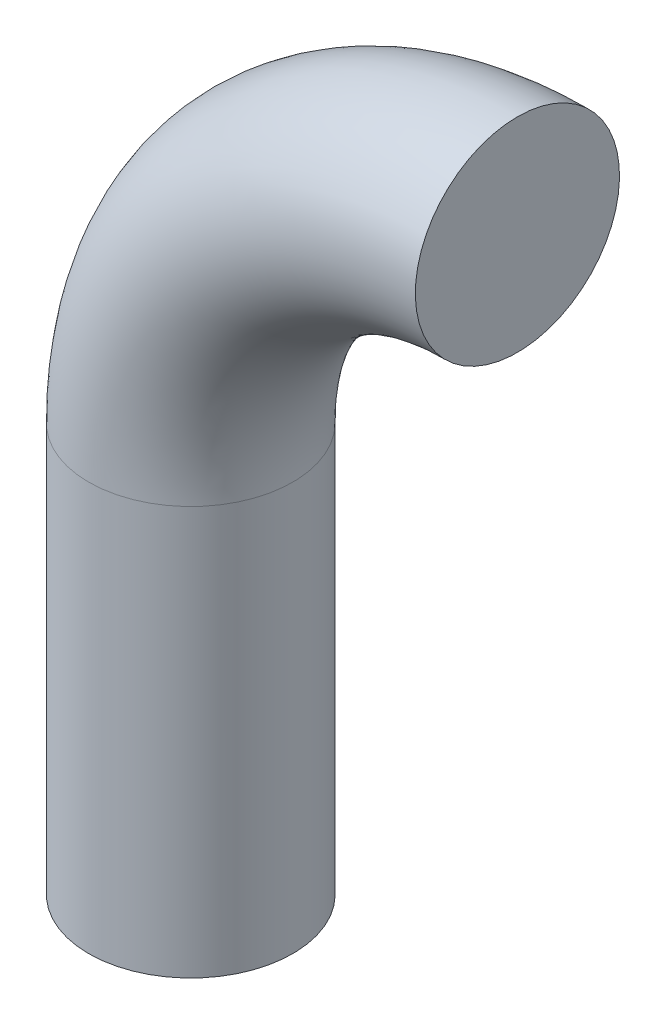
SolidWorks part; units mm, degrees
material "ABS PC"
ref_plane "Front Plane" through (0, 0, 0) normal (0, 0, 1) x (1, 0, 0)
ref_plane "Top Plane" through (0, 0, 0) normal (0, 1, 0) x (1, 0, 0)
ref_plane "Right Plane" through (0, 0, 0) normal (1, 0, 0) x (0, 0, -1)
sketch "Sketch1" plane through (0, 0, 0) normal (0, 0, 1) x (1, 0, 0)
  line L0 (0, 0) -> (0, 100)
  arc A0 (0, 100) -> (80, 180) centre (80, 100) cw
  dimension "D2" = 80
  dimension "D1" = 100
sketch "Sketch2" plane through (0, 0, 0) normal (0, 1, 0) x (1, 0, 0)
  circle A0 centre (0, 0) radius 25
  dimension "D1" = 50
sweep "Sweep1" add profiles "Sketch2" path "Sketch1"
shell "Shell1" thickness 3
